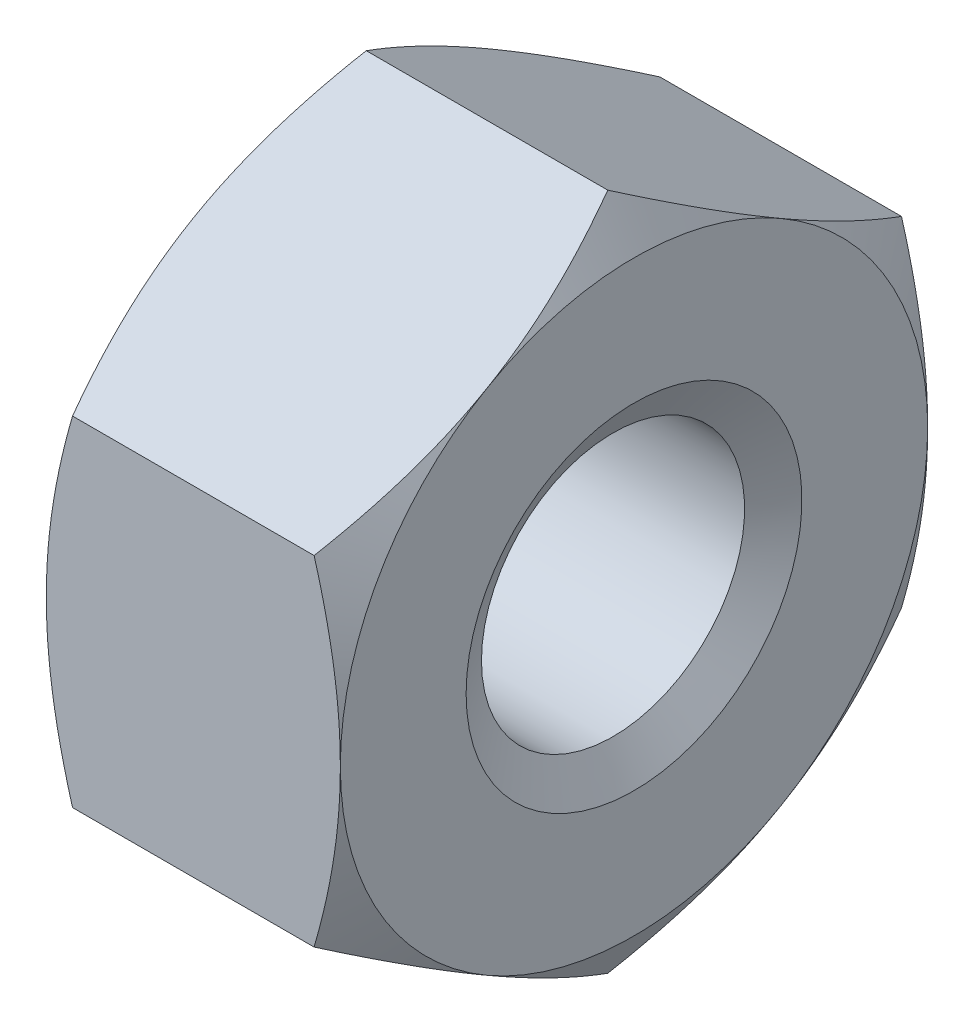
SolidWorks part; units mm, degrees
ref_plane "Front Plane" through (0, 0, 0) normal (0, 0, 1) x (1, 0, 0)
ref_plane "Top Plane" through (0, 0, 0) normal (0, 1, 0) x (1, 0, 0)
ref_plane "Right Plane" through (0, 0, 0) normal (1, 0, 0) x (0, 0, -1)
ref_plane "Plane1"
sketch "Sketch1" plane through (0, 0, 0) normal (1, 0, 0) x (0, 1, 0)
  line L0 (-6.4158, 0) -> (-3.2079, 5.5562)
  line L1 (-3.2079, 5.5562) -> (3.2079, 5.5562)
  line L2 (3.2079, 5.5562) -> (6.4158, 0)
  line L3 (6.4158, 0) -> (3.2079, -5.5562)
  line L4 (3.2079, -5.5562) -> (-3.2079, -5.5563)
  line L5 (-3.2079, -5.5563) -> (-6.4158, 0)
  dimension "D1" = 12.8316
extrude "Body" add sketch "Sketch1" along normal blind 5.5626
ref_plane "Plane2"
sketch "Sketch2" plane through (0, 0, 0) normal (0, 0, 1) x (1, 0, 0)
  line L0 (0, 6.4158) -> (0, 5.5563)
  line L1 (0, 5.5563) -> (0.4963, 6.4158)
  line L2 (0.4963, 6.4158) -> (0, 6.4158)
  line L3 (-1.1125, 0) -> (6.6751, 0) construction
  line L4 (5.0663, 6.4158) -> (5.5626, 5.5563)
  line L5 (5.5626, 5.5563) -> (5.5626, 6.4158)
  line L6 (5.5626, 6.4158) -> (5.0663, 6.4158)
  line L7 (0, 6.4158) -> (0, 3.2079) construction
  line L8 (5.5626, 6.4158) -> (5.5626, 3.2079) construction
  dimension "D1" = 150
  dimension "D2" = 150
  dimension "D3" = 90
  dimension "D4" = 120
revolve "Chamfer1" cut sketch "Sketch2" angle 360 about L3
hole_wizard "Thread" positions "Sketch4" profile "Sketch3" legacy end condition through all
sketch "Sketch4" plane through (5.5626, 0, 0) normal (1, 0, 0) x (0, 0, -1)
  point P1 (0, 0)
sketch "Sketch3" plane through (5.5626, 0, 0) normal (0, 1, 0) x (0, 0, -1)
  line L0 (0, 0) -> (0, 5.5626)
  line L1 (0, 5.5626) -> (2.4892, 5.5626)
  line L2 (2.4892, 5.5626) -> (2.4892, 0)
  line L3 (2.4892, 0) -> (0, 0)
  line L4 (0, 110) -> (0, -10) construction
  dimension "Diameter" = 4.9784
  dimension "Depth" = 5.5626
cosmetic thread "Cosmetic Thread1"
chamfer "Chamfer2" distance 0.6874 angle 30 1 edges at (5.5626, 0, -2.4892)
chamfer "Chamfer3" distance 0.6874 angle 30 1 edges at (0, 0, -2.4892)
